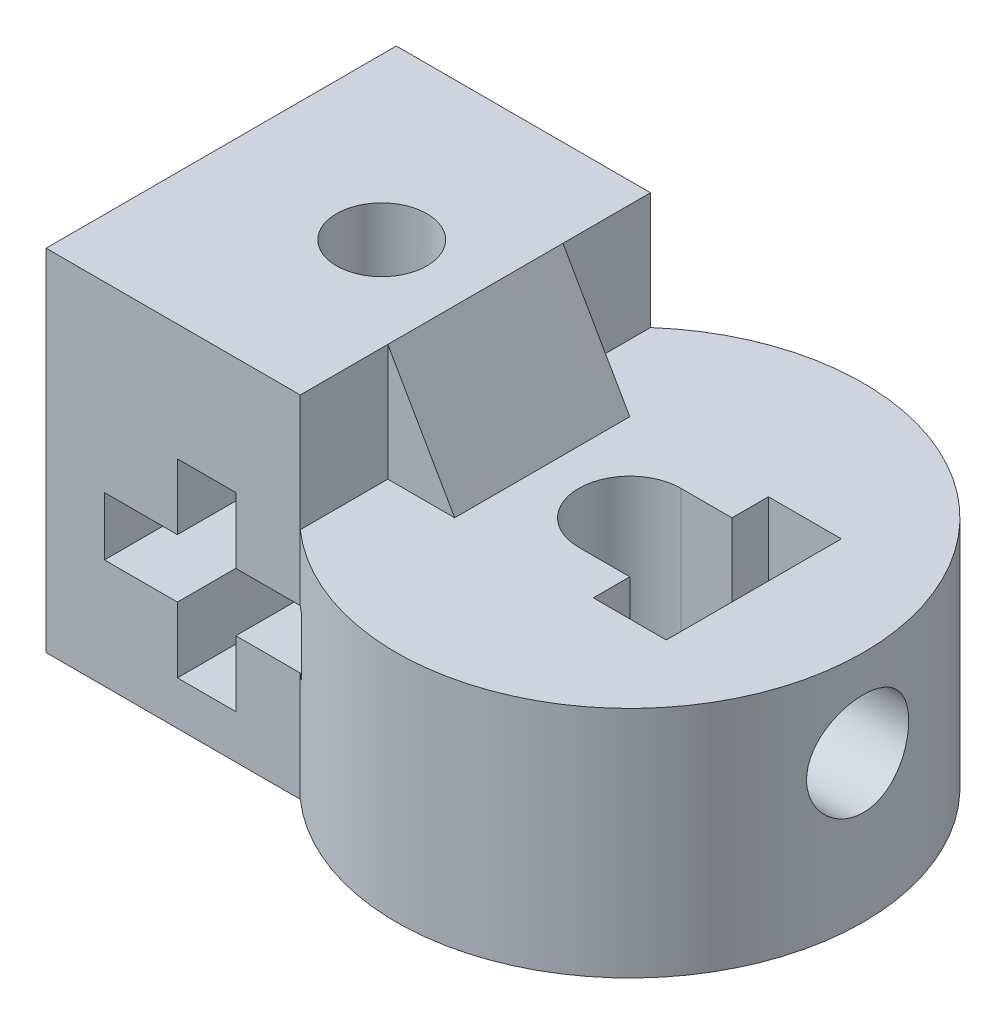
SolidWorks part; units mm, degrees
ref_plane "前视基准面" through (0, 0, 0) normal (0, 0, 1) x (1, 0, 0)
ref_plane "上视基准面" through (0, 0, 0) normal (0, 1, 0) x (1, 0, 0)
ref_plane "右视基准面" through (0, 0, 0) normal (1, 0, 0) x (0, 0, -1)
sketch "草图1" plane through (0, 0, 0) normal (0, 1, 0) x (1, 0, 0)
  line L0 (1.75, 3) -> (1.75, 1.75)
  line L1 (1.75, -3) -> (4.25, -3)
  line L2 (4.25, -3) -> (4.25, 3)
  line L3 (4.25, 3) -> (1.75, 3)
  line L4 (0, 1.75) -> (1.75, 1.75)
  line L5 (0, -1.75) -> (1.75, -1.75)
  line L6 (0, 0) -> (4.25, 0) construction
  line L7 (1.75, -1.75) -> (1.75, -3)
  line L8 (-14, 0) -> (0, 0) construction
  line L10 (-14, 6) -> (-5.2915, 6)
  line L11 (-14, 6) -> (-14, -6)
  line L12 (-14, -6) -> (-5.2915, -6)
  arc A0 (-5.2915, -6) -> (-5.2915, 6) centre (0, 0) ccw
  arc A1 (0, 1.75) -> (0, -1.75) centre (0, 0) ccw
  dimension "D1" = 16
  dimension "D2" = 3.5
  dimension "D3" = 2.5
  dimension "D4" = 6
  dimension "D5" = 14
  dimension "D6" = 12
extrude "凸台-拉伸1" add sketch "草图1" along normal blind 8
sketch "草图4" plane through (0, 0, 0) normal (0, -1, 0) x (1, 0, 0)
  circle A0 centre (0, 0) radius 7
  dimension "D1" = 14
extrude "切除-拉伸3" cut sketch "草图4" against normal blind 2
sketch "草图7" plane through (0, 8, 0) normal (0, 1, 0) x (1, 0, 0)
  line L1 (-14, 6) -> (-5.2915, 6)
  line L2 (-14, 6) -> (-14, -6)
  line L3 (-14, -6) -> (-5.2915, -6)
  line L4 (-5.2915, 6) -> (-5.2915, -6)
extrude "凸台-拉伸2" add sketch "草图7" along normal blind 4
sketch "草图2" plane through (4.25, 0, 0) normal (-1, 0, 0) x (0, 0, 1)
  line L2 (-7, 2) -> (7, 2) construction
  circle A0 centre (0, 5) radius 1.75
  dimension "D1" = 3.5
  dimension "D2" = 3
extrude "切除-拉伸1" cut sketch "草图2" against normal through all
sketch "草图3" plane through (-19, 0, 6) normal (0, 0, -1) x (-1, 0, 0)
  line L5 (-5, 12) -> (-5, 0) construction
  line L6 (-11.5, 1.5) -> (-9.5, 1.5)
  line L12 (-5, 0) -> (-13.7085, 0) construction
  line L14 (-11.5, 1.5) -> (-11.5, 3.75)
  line L15 (-11.5, 8) -> (-9.5, 8)
  line L16 (-9.5, 1.5) -> (-9.5, 3.75)
  line L19 (-14, 4.75) -> (-7, 4.75) construction
  line L20 (-13.7085, 8) -> (-5, 8) construction
  line L21 (-14, 5.75) -> (-11.5, 5.75)
  line L22 (-14, 5.75) -> (-14, 3.75)
  line L23 (-14, 3.75) -> (-11.5, 3.75)
  line L24 (-7, 5.75) -> (-7, 3.75)
  line L31 (-9.5, 5.75) -> (-9.5, 8)
  line L32 (-9.5, 5.75) -> (-7, 5.75)
  line L34 (-11.5, 5.75) -> (-11.5, 8)
  line L35 (-9.5, 3.75) -> (-7, 3.75)
  point P0 (-11.5, 3.3306)
  point P5 (-11.5, 3.3306)
  dimension "D1" = 2
  dimension "D2" = 2
  dimension "D3" = 7
  dimension "D4" = 6.5
  dimension "D5" = 2
  dimension "D6" = 1.5
  dimension "D7" = 0
extrude "切除-拉伸2" cut sketch "草图3" along normal through all and the other way through all
sketch "草图5" plane through (0, 12, 0) normal (0, 1, 0) x (1, 0, 0)
  line L0 (-14, 0) -> (0, 0) construction
  line L3 (-8.5, 0) -> (-8.5, -6) construction
  line L4 (-9.5, -6) -> (-7.5, -6) construction
  circle A0 centre (-8.5, 0) radius 1.55
  point P7 (-8.5, -6)
  dimension "D1" = 3.1
extrude "切除-拉伸4" cut sketch "草图5" against normal up to next
sketch "草图8" plane through (0, 0, 0) normal (0, 0, 1) x (1, 0, 0)
  line L0 (-5.2915, 12) -> (-3, 8)
  line L1 (8, 8) -> (-5.2915, 8) construction
rib "筋1" sketch "草图8" sketch "草图8" thickness 6 extrusion direction parallel to sketch draft on no parameters "D1"=6
